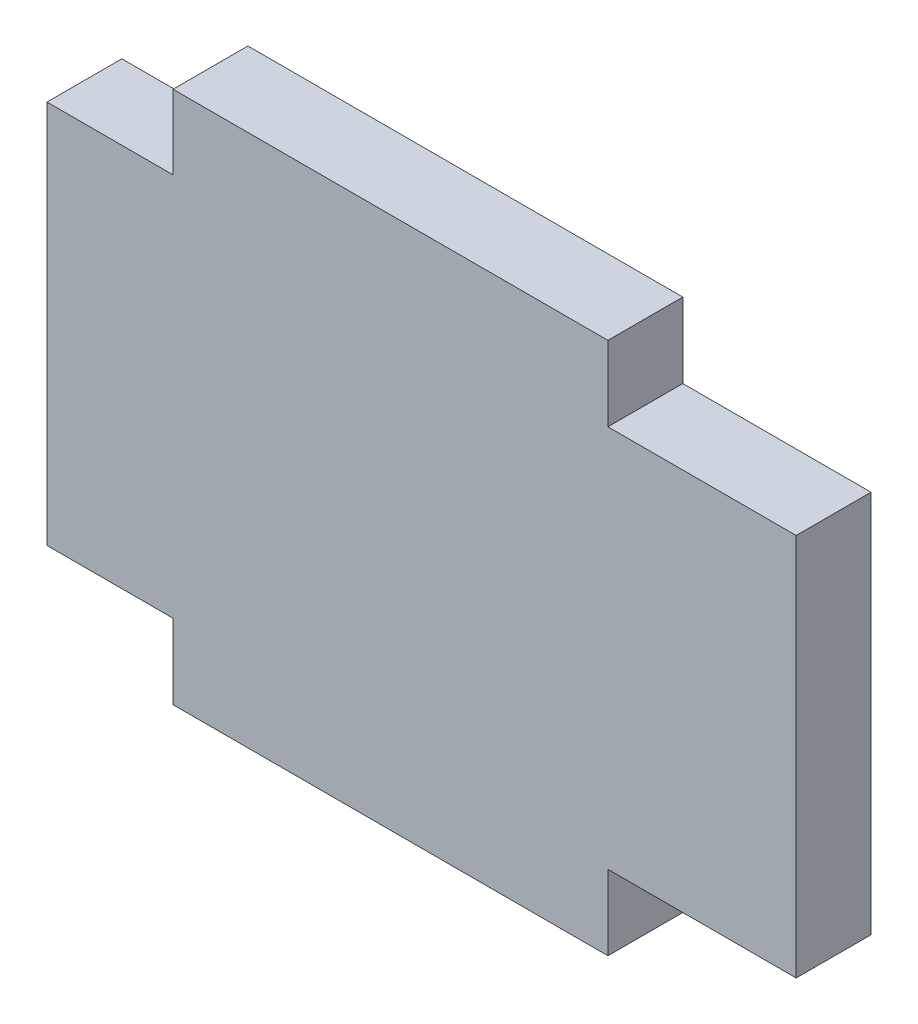
SolidWorks part; units mm, degrees
ref_plane "Front Plane" through (0, 0, 0) normal (0, 0, 1) x (1, 0, 0)
ref_plane "Top Plane" through (0, 0, 0) normal (0, 1, 0) x (1, 0, 0)
ref_plane "Right Plane" through (0, 0, 0) normal (1, 0, 0) x (0, 0, -1)
sketch "Sketch1" plane through (0, 0, 0) normal (0, 0, 1) x (-1, 0, 0)
  line L0 (87.6936, 20.7069) -> (87.6936, 25.7357)
  line L1 (87.6936, 25.7357) -> (96.2464, 25.7357)
  line L2 (87.6945, 51.7869) -> (87.6945, 56.8669)
  line L3 (87.6945, 56.8669) -> (58.1912, 56.8669)
  line L4 (58.1912, 56.8669) -> (58.1912, 51.7869)
  line L5 (58.1912, 51.7869) -> (45.4194, 51.7869)
  line L6 (45.4194, 51.7869) -> (45.4194, 25.7869)
  line L7 (58.1904, 25.7869) -> (45.4194, 25.7869)
  line L8 (58.1904, 25.7869) -> (58.1904, 20.7069)
  line L9 (58.1904, 20.7069) -> (87.6936, 20.7069)
  line L10 (96.2464, 25.7357) -> (96.2464, 51.7869)
  line L11 (96.2464, 51.7869) -> (87.6945, 51.7869)
extrude "Boss-Extrude1" add sketch "Sketch1" along normal blind 5.08 contours L9 L0 L1 L10 L11 L2 L3 L4 L5 L6 L7 L8
